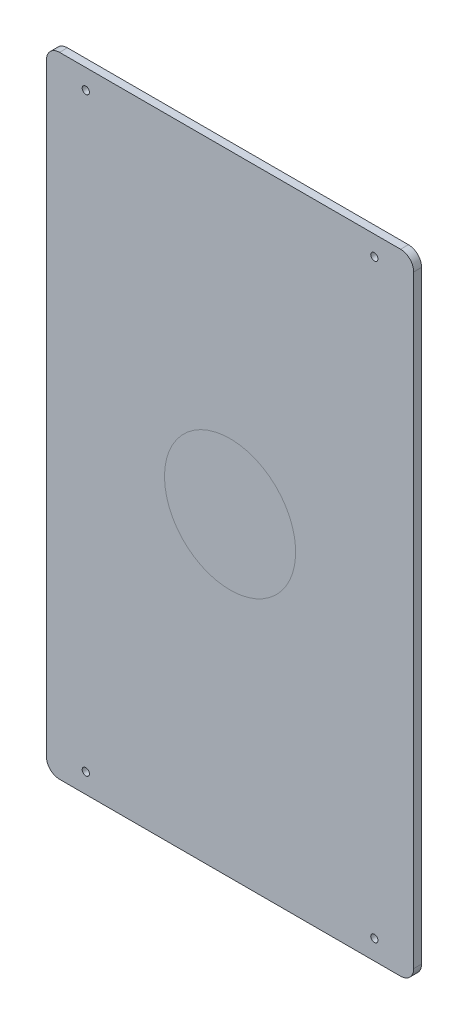
SolidWorks part; units mm, degrees
material "ABS"
ref_plane "Front" through (0, 0, 0) normal (0, 0, 1) x (1, 0, 0)
ref_plane "Top" through (0, 0, 0) normal (0, 1, 0) x (1, 0, 0)
ref_plane "Right" through (0, 0, 0) normal (1, 0, 0) x (0, 0, -1)
sketch "草图1" plane through (0, 0, 0) normal (0, 0, 1) x (1, 0, 0)
  line L0 (-30, 15) -> (-30, -465)
  line L1 (0, 0) -> (220, 0) construction
  line L2 (0, 0) -> (0, -450) construction
  line L3 (0, -450) -> (220, -450) construction
  line L4 (220, 0) -> (220, -450) construction
  line L5 (-30, -465) -> (250, -465)
  line L6 (250, 15) -> (250, -465)
  line L7 (-30, 15) -> (250, 15)
  circle A0 centre (0, 0) radius 2.75
  circle A1 centre (220, 0) radius 2.75
  circle A2 centre (220, -450) radius 2.75
  circle A3 centre (0, -450) radius 2.75
  dimension "D4" = 5.5
  dimension "D1" = 220
  dimension "D2" = 450
  dimension "D3" = 30
  dimension "D5" = 30
  dimension "D6" = 15
  dimension "D7" = 15
extrude "凸台-拉伸1" add sketch "草图1" along normal blind 6
fillet "圆角1" radius 10 4 edges at (250, -465, 3) (-30, -465, 3) (-30, 15, 3) (250, 15, 3)
ref_plane "基准面1" through (0, 0, 16) normal (0, 0, 1) x (1, 0, 0)
sketch "草图3" plane through (0, 0, 16) normal (0, 0, 1) x (1, 0, 0)
  line L0 (110, 15) -> (110, -465) construction
  line L3 (240, 15) -> (-20, 15) construction
  line L4 (-20, -465) -> (240, -465) construction
  circle A0 centre (110, -225) radius 50
  dimension "D1" = 100
split line "分割线2"
